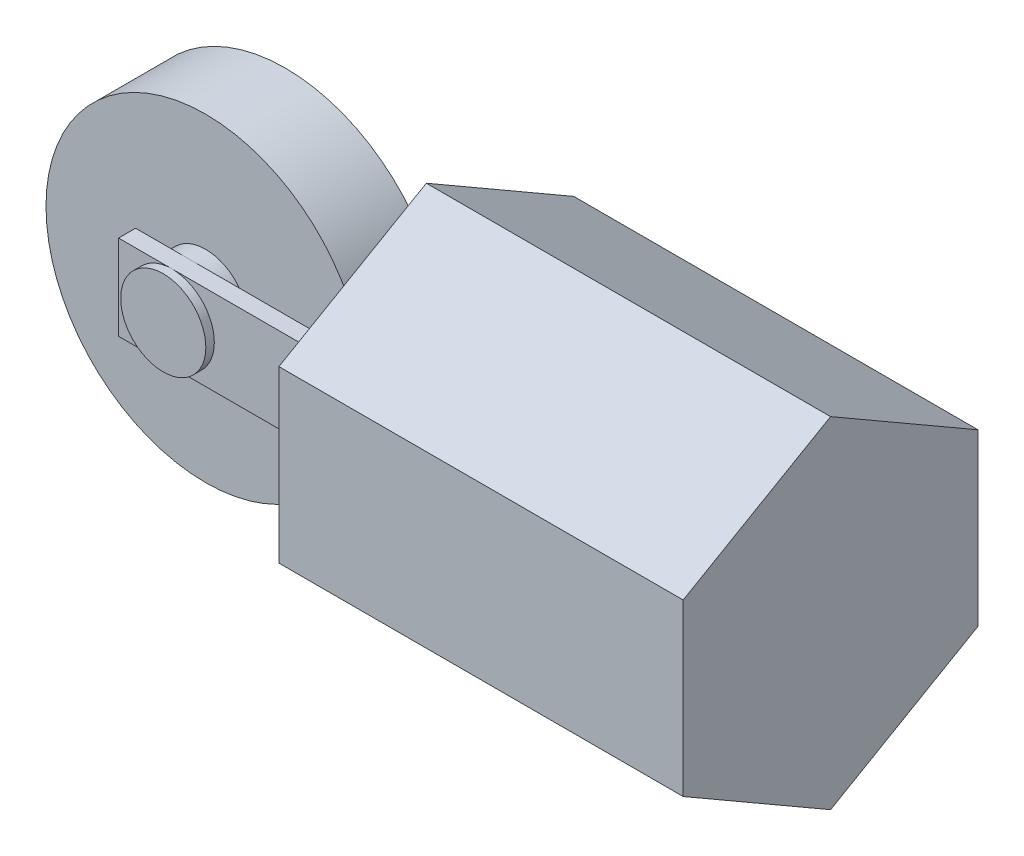
SolidWorks part; units mm, degrees
ref_plane "Front Plane" through (0, 0, 0) normal (1, 0, 0) x (0, 1, 0)
ref_plane "Top Plane" through (0, 0, 0) normal (0, 0, 1) x (0, 1, 0)
ref_plane "Right Plane" through (0, 0, 0) normal (0, 1, 0) x (-1, 0, 0)
sketch "Sketch3" plane through (0, 0, 0) normal (0, 0, 1) x (0, 1, 0)
  circle A0 centre (0, 0) radius 9.525
  dimension "D1" = 19.05
extrude "Boss-Extrude1" add sketch "Sketch3" along normal mid plane 4.7625
ref_plane "Plane2" through (9.525, 0, 0) normal (1, 0, 0) x (0, 1, 0)
sketch "Sketch6" plane through (9.525, 0, 0) normal (1, 0, 0) x (0, 1, 0)
  line L2 (-5.08, 0) -> (-2.54, -4.3994)
  line L3 (-2.54, -4.3994) -> (2.54, -4.3994)
  line L4 (2.54, -4.3994) -> (5.08, 0)
  line L5 (5.08, 0) -> (2.54, 4.3994)
  line L6 (2.54, 4.3994) -> (-2.54, 4.3994)
  line L7 (-2.54, 4.3994) -> (-5.08, 0)
  circle A0 centre (0, 0) radius 4.3994 construction
  dimension "D1" = 5.08
  dimension "D2" = 8.7988
extrude "Boss-Extrude4" add sketch "Sketch6" along normal blind 25.4 separate body
sketch "Sketch7" plane through (9.525, 0, 0) normal (-1, 0, 0) x (0, -1, 0)
  line L0 (-2.54, 4.3994) -> (2.54, 4.3994)
  line L1 (-2.54, 4.3994) -> (-2.54, 3.3834)
  line L2 (2.54, 4.3994) -> (2.54, 3.3834)
  line L3 (-2.54, 3.3834) -> (2.54, 3.3834)
  line L4 (-2.54, -4.3994) -> (2.54, -4.3994)
  line L5 (-2.54, -4.3994) -> (-2.54, -3.3834)
  line L6 (2.54, -4.3994) -> (2.54, -3.3834)
  line L7 (-2.54, -3.3834) -> (2.54, -3.3834)
  dimension "D1" = 1.016
  dimension "D2" = 1.016
extrude "Boss-Extrude5" add sketch "Sketch7" along normal blind 12.7
sketch "Sketch10" plane through (9.525, 0, 0) normal (-1, 0, 0) x (0, -1, 0)
  line L0 (-2.54, 4.3994) -> (-5.08, 0)
  line L1 (-5.08, 0) -> (-2.54, 4.3994) construction
  line L2 (-5.08, 0) -> (-2.54, -4.3994)
  line L3 (-2.54, -4.3994) -> (-2.54, -3.3834)
  line L4 (-2.54, -3.3834) -> (2.54, -3.3834)
  line L5 (2.54, -3.3834) -> (2.54, -4.3994)
  line L6 (2.54, -4.3994) -> (5.08, 0)
  line L7 (5.08, 0) -> (2.54, 4.3994)
  line L8 (2.54, 4.3994) -> (2.54, 3.3834)
  line L9 (2.54, 3.3834) -> (2.54, 4.3994) construction
  line L10 (2.54, 3.3834) -> (-2.54, 3.3834)
  line L11 (-2.54, 3.3834) -> (-2.54, 4.3994)
  dimension "D1" = 5.08
extrude "Cut-Extrude1" cut sketch "Sketch10" against normal blind 1.27
sketch "Sketch11" plane through (0, 0, 4.3994) normal (0, 0, 1) x (1, 0, 0)
  circle A0 centre (0, 0) radius 2.54
  dimension "D1" = 5.08
extrude "Boss-Extrude6" add sketch "Sketch11" along normal blind 0.508 and the other way blind 9.398
sketch "Sketch12" plane through (34.925, 0, 0) normal (1, 0, 0) x (0, 1, 0)
  line L2 (-10.16, 0) -> (-5.08, -8.7988)
  line L3 (-5.08, -8.7988) -> (5.08, -8.7988)
  line L4 (5.08, -8.7988) -> (10.16, 0)
  line L5 (10.16, 0) -> (5.08, 8.7988)
  line L6 (5.08, 8.7988) -> (-5.08, 8.7988)
  line L7 (-5.08, 8.7988) -> (-10.16, 0)
  circle A0 centre (0, 0) radius 8.7988 construction
  dimension "D1" = 10.16
  dimension "D2" = 8.7988
extrude "Boss-Extrude7" add sketch "Sketch12" against normal blind 24.13
